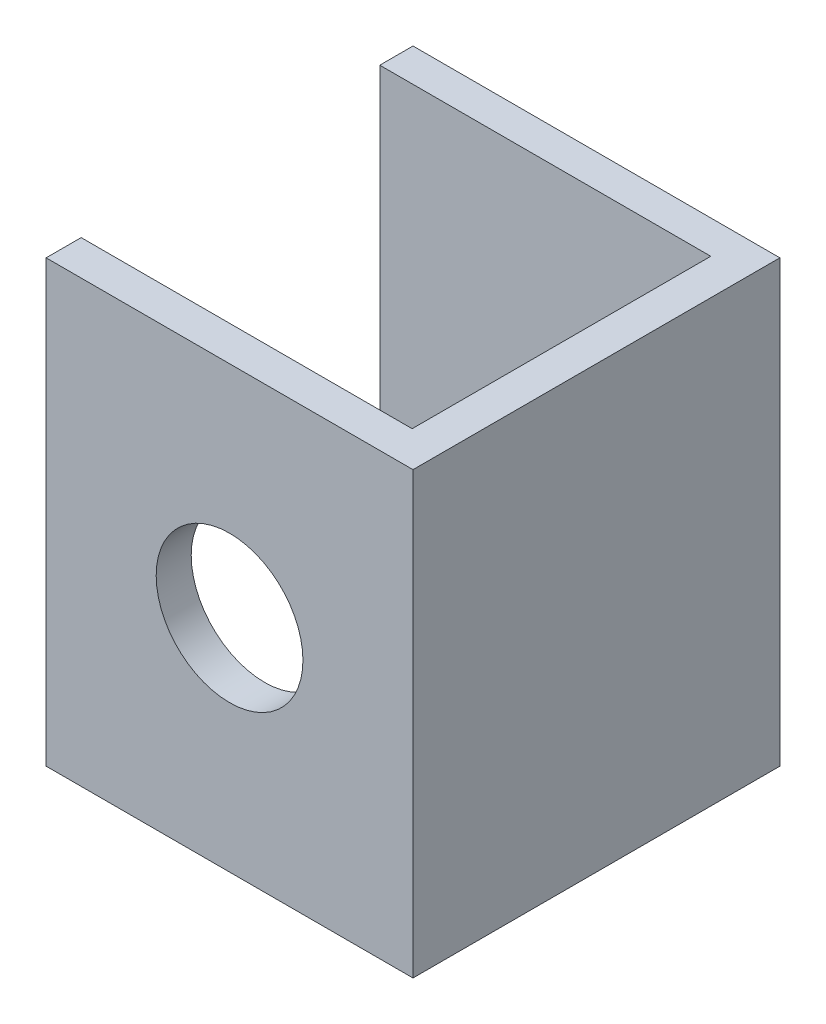
SolidWorks part; units mm, degrees
ref_plane "Front Plane" through (0, 0, 0) normal (0, 0, 1) x (1, 0, 0)
ref_plane "Top Plane" through (0, 0, 0) normal (0, 1, 0) x (1, 0, 0)
ref_plane "Right Plane" through (0, 0, 0) normal (1, 0, 0) x (0, 0, -1)
sketch "Sketch3" plane through (0, 0, 0) normal (1, 0, 0) x (0, 0, -1)
  line L1 (26.8422, -38.8167) -> (-36.6578, -38.8167)
  line L2 (26.8422, -38.8167) -> (26.8422, 37.3833)
  line L3 (26.8422, 37.3833) -> (-36.6578, 37.3833)
  line L4 (-36.6578, -38.8167) -> (-36.6578, 37.3833)
extrude "Boss-Extrude1" add sketch "Sketch3" along normal blind 63.5
sketch "Sketch4" plane through (0, 37.3833, 0) normal (0, 1, 0) x (1, 0, 0)
  line L0 (0, 21.0937) -> (63.5, 21.0937)
  line L1 (0, 26.8422) -> (0, -36.6578) construction
  line L2 (63.5, 26.8422) -> (63.5, -36.6578) construction
  line L3 (57.2888, 26.8422) -> (57.2888, -36.6578)
  line L4 (63.5, 26.8422) -> (0, 26.8422) construction
  line L5 (63.5, -36.6578) -> (0, -36.6578) construction
  line L6 (63.5, -30.5946) -> (0, -30.5946)
  line L9 (0, -30.5946) -> (0, 21.0937)
sketch "Sketch20" plane through (0, -38.8167, 0) normal (0, -1, 0) x (-1, 0, 0)
  line L0 (0, 21.0937) -> (-63.5, 21.0937) construction
  line L1 (0, -30.5946) -> (-57.2888, -30.5946)
  line L2 (0, -30.5946) -> (0, 21.0937)
  line L3 (0, 21.0937) -> (-57.2888, 21.0937)
  line L4 (-57.2888, -30.5946) -> (-57.2888, 21.0937)
  line L5 (-57.2888, 26.8422) -> (-57.2888, -36.6578) construction
extrude "Cut-Extrude2" cut sketch "Sketch20" against normal through all
sketch "Sketch21" plane through (0, 0, 36.6578) normal (0, 0, 1) x (1, 0, 0)
  line L0 (63.5, 37.3833) -> (63.5, -38.8167) construction
  line L1 (63.5, -38.8167) -> (0, -38.8167) construction
  circle A0 centre (31.75, -0.7167) radius 12.7
  dimension "D1" = 31.75
  dimension "D2" = 38.1
extrude "Cut-Extrude4" cut sketch "Sketch21" against normal up to surface (6.0632 mm away) contours A0 up to face at (28.6444, -0.7167, 30.5946)
